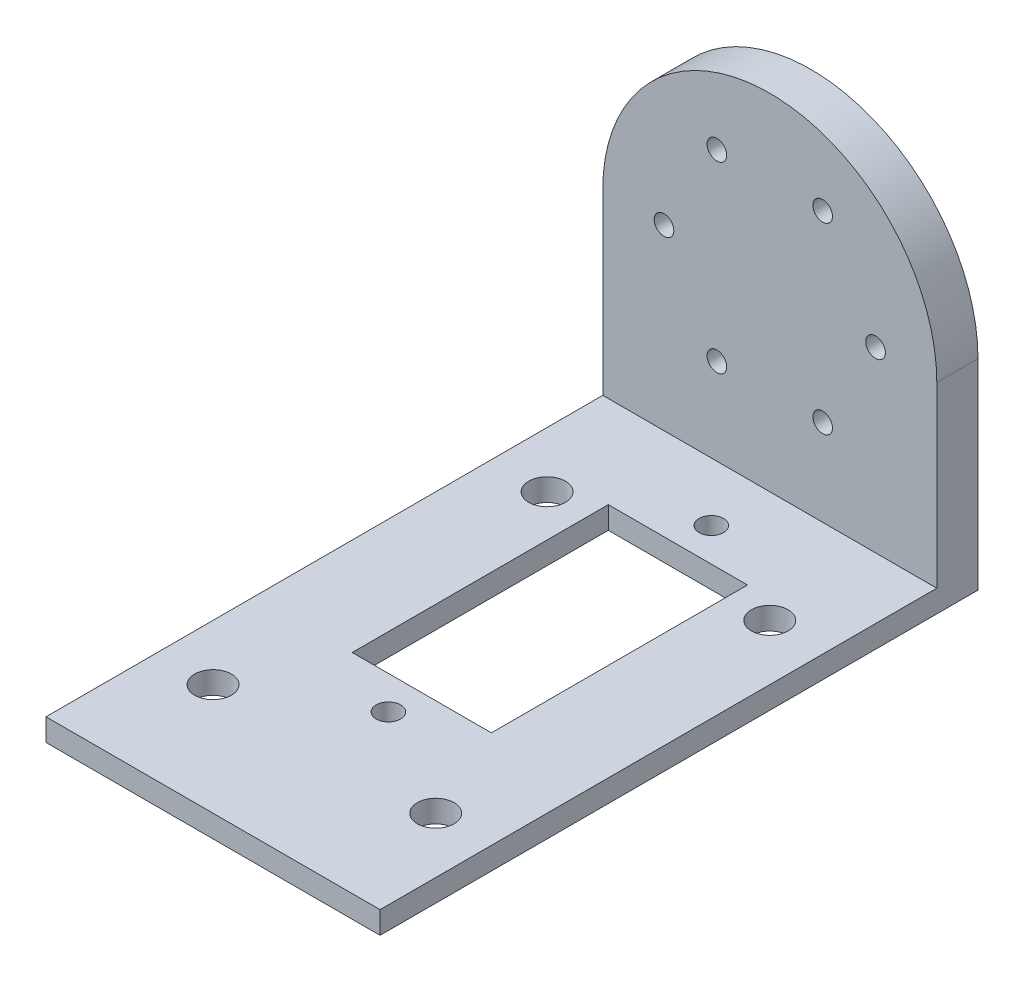
SolidWorks part; units mm, degrees
ref_plane "前视基准面" through (0, 0, 0) normal (0, 0, 1) x (1, 0, 0)
ref_plane "上视基准面" through (0, 0, 0) normal (0, 1, 0) x (1, 0, 0)
ref_plane "右视基准面" through (0, 0, 0) normal (1, 0, 0) x (0, 0, -1)
sketch "草图1" plane through (0, 0, 0) normal (0, 0, 1) x (1, 0, 0)
  line L0 (-15, 0) -> (-15, -18)
  line L1 (-15, -18) -> (15, -18)
  line L2 (15, -18) -> (15, 0)
  arc A0 (-15, 0) -> (15, 0) centre (0, 0) cw
  circle A1 centre (9.5, 0) radius 0.88
  circle A2 centre (4.75, -8.2272) radius 0.88
  circle A3 centre (-4.75, -8.2272) radius 0.88
  circle A4 centre (-9.5, 0) radius 0.88
  circle A5 centre (-4.75, 8.2272) radius 0.88
  circle A6 centre (4.75, 8.2272) radius 0.88
  point P20 (0, 0)
  dimension "D1" = 6
  dimension "D2" = 1.76
extrude "凸台-拉伸1" add sketch "草图1" along normal blind 3.7
ref_plane "基准面2" through (0, -18, 0) normal (0, 1, 0) x (1, 0, 0)
sketch "草图3" plane through (0, -18, 0) normal (0, 1, 0) x (1, 0, 0)
  line L0 (-15, -3.7) -> (15, -3.7)
  line L1 (15, -3.7) -> (15, -53.7)
  line L2 (15, -53.7) -> (-15, -53.7)
  line L3 (-15, -53.7) -> (-15, -3.7)
  line L4 (0, 0) -> (0, -11.3227) construction
  line L5 (-15, -28.7) -> (9.1501, -28.7) construction
  line L6 (0, -28.7) -> (0, -19.3266) construction
  line L7 (-6.25, -28.7) -> (-6.25, -11.95)
  line L8 (-6.25, -11.95) -> (6.25, -11.95)
  line L9 (-6.25, -28.7) -> (-6.25, -34.95)
  line L10 (-6.25, -34.95) -> (6.25, -34.95)
  line L11 (6.25, -28.7) -> (6.25, -34.95)
  line L12 (6.25, -28.7) -> (6.25, -11.95)
  circle A0 centre (-10, -13.7) radius 1.65
  circle A1 centre (10, -13.7) radius 1.65
  circle A2 centre (10, -43.7) radius 1.65
  circle A3 centre (-10, -43.7) radius 1.65
  circle A4 centre (0, -8.95) radius 1.1
  circle A5 centre (0, -37.95) radius 1.1
  point P27 (0, -34.95)
  point P29 (0, -11.95)
  dimension "D1" = 3
  dimension "D2" = 3
extrude "凸台-拉伸2" add sketch "草图3" along normal blind 2
